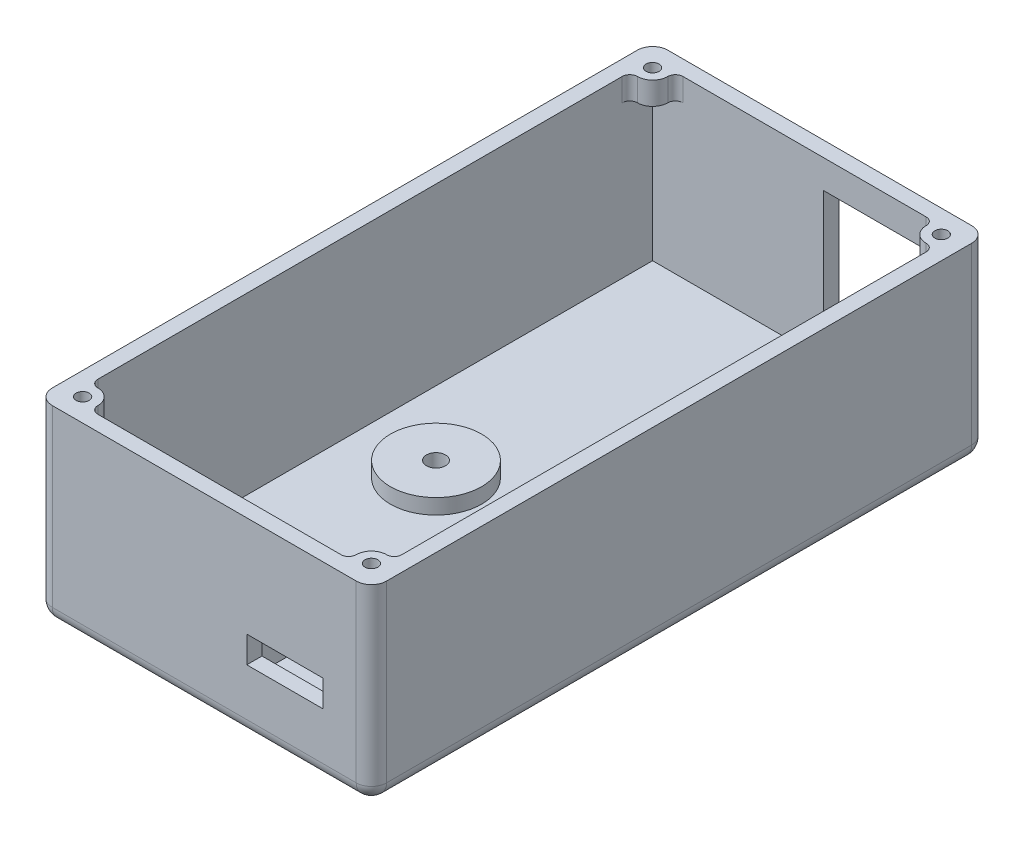
SolidWorks part; units mm, degrees
ref_plane "前视基准面" through (0, 0, 0) normal (0, 0, 1) x (1, 0, 0)
ref_plane "上视基准面" through (0, 0, 0) normal (0, 1, 0) x (1, 0, 0)
ref_plane "右视基准面" through (0, 0, 0) normal (1, 0, 0) x (0, 0, -1)
sketch "草图1" plane through (0, 0, 0) normal (0, 1, 0) x (1, 0, 0)
  line L1 (-22, 38) -> (22, 38)
  line L2 (-22, 38) -> (-22, -43)
  line L3 (-22, -43) -> (22, -43)
  line L4 (22, 38) -> (22, -43)
  dimension "D1" = 81
  dimension "D2" = 38
  dimension "D3" = 44
  dimension "D4" = 22
extrude "凸台-拉伸1" add sketch "草图1" along normal blind 25
shell "抽壳1" thickness 2
fillet "圆角1" radius 2 8 edges at (0, 0, -38) (0, 0, 43) (-22, 0, 2.5) (22, 0, 2.5) (-22, 12.5, 43) (-22, 12.5, -38) (22, 12.5, -38) (22, 12.5, 43)
sketch "草图2" plane through (0, 2, 0) normal (0, 1, 0) x (1, 0, 0)
  line L0 (20, 36) -> (-20, 36) construction
  line L1 (20, -41) -> (20, 36) construction
  line L2 (20, 36) -> (-20, 36) construction
  circle A0 centre (4.8, 16.9) radius 0.8
  circle A1 centre (16.1, -9.5) radius 0.9
  dimension "D1" = 19.1
  dimension "D3" = 45.5
  dimension "D2" = 15.2
  dimension "D4" = 3.9
extrude "切除-拉伸1" cut sketch "草图2" against normal blind 24
sketch "草图3" plane through (0, 2, 0) normal (0, 1, 0) x (1, 0, 0)
  line L1 (-20, 36) -> (-20, -41) construction
  line L2 (-20, -41) -> (20, -41) construction
  circle A0 centre (-9.5, -3) radius 1.25
  dimension "D3" = 2.5
  dimension "D1" = 10.5
  dimension "D2" = 38
extrude "切除-拉伸2" cut sketch "草图3" against normal blind 24
sketch "草图4" plane through (0, 2, 0) normal (0, 1, 0) x (1, 0, 0)
  circle A0 centre (-9.5, -3) radius 6
extrude "凸台-拉伸2" add sketch "草图4" along normal blind 2
sketch "草图6" plane through (0, 0, 0) normal (0, -1, 0) x (1, 0, 0)
  circle A0 centre (-9.5, 3) radius 1.25
extrude "切除-拉伸4" cut sketch "草图6" against normal blind 13.2
sketch "草图7" plane through (0, 0, -38) normal (0, 0, -1) x (-1, 0, 0)
  line L0 (20, 0) -> (-20, 0) construction
  line L1 (-18, 21.25) -> (-2.5, 21.25)
  line L2 (-18, 21.25) -> (-18, 3.75)
  line L3 (-18, 3.75) -> (-2.5, 3.75)
  line L4 (-2.5, 21.25) -> (-2.5, 3.75)
  line L5 (-22, 2) -> (-22, 25) construction
  dimension "D1" = 17.5
  dimension "D2" = 3.75
  dimension "D3" = 4
  dimension "D4" = 15.5
extrude "切除-拉伸5" cut sketch "草图7" against normal blind 13.2
sketch "草图9" plane through (0, 2, 0) normal (0, 1, 0) x (1, 0, 0)
  line L0 (-20, -41) -> (20, -41) construction
  line L1 (1.2, -34.5) -> (20, -34.5)
  line L2 (1.2, -34.5) -> (1.2, -41)
  line L3 (1.2, -41) -> (20, -41)
  line L4 (20, -34.5) -> (20, -41)
  line L5 (-20, -41) -> (20, -41) construction
  line L6 (22, -41) -> (22, 36) construction
  circle A0 centre (18.1, -37.9) radius 0.9
  circle A1 centre (3.1, -37.9) radius 0.9
  dimension "D7" = 1.8
  dimension "D8" = 1.8
  dimension "D1" = 15
  dimension "D2" = 1.9
  dimension "D3" = 3.1
  dimension "D4" = 6.5
  dimension "D5" = 1.9
  dimension "D6" = 2
  dimension "D9" = 3.1
  dimension "D10" = 18.8
extrude "凸台-拉伸3" add sketch "草图9" along normal blind 8 contours L2 L1 L4 L3 | A1 | A0
sketch "草图11" plane through (0, 10, 0) normal (0, 1, 0) x (1, 0, 0)
  line L0 (1.2, -34.5) -> (20, -34.5) construction
  line L1 (5.1, -34.5) -> (16.1, -34.5)
  line L2 (5.1, -34.5) -> (5.1, -41)
  line L3 (5.1, -41) -> (16.1, -41)
  line L4 (16.1, -34.5) -> (16.1, -41)
  line L5 (-20, -41) -> (20, -41) construction
  dimension "D1" = 11
  dimension "D2" = 3.9
extrude "切除-拉伸6" cut sketch "草图11" against normal blind 4
sketch "草图12" plane through (0, 0, 43) normal (0, 0, 1) x (1, 0, 0)
  line L0 (20, 0) -> (-20, 0) construction
  line L1 (5.6, 11.75) -> (15.6, 11.75)
  line L2 (5.6, 11.75) -> (5.6, 8.25)
  line L3 (5.6, 8.25) -> (15.6, 8.25)
  line L4 (15.6, 11.75) -> (15.6, 8.25)
  line L5 (22, 25) -> (22, 2) construction
  dimension "D1" = 10
  dimension "D2" = 3.5
  dimension "D3" = 8.25
  dimension "D4" = 6.4
extrude "切除-拉伸7" cut sketch "草图12" against normal blind 4
fillet "圆角2" radius 2 3 edges at (1.2, 2, 37.75) (10.6, 2, 34.5) (1.2, 6, 34.5)
sketch "草图14" plane through (0, 0, 0) normal (0, -1, 0) x (1, 0, 0)
  circle A0 centre (-9.5, 3) radius 1.25
extrude "凸台-拉伸4" add sketch "草图14" against normal blind 1
sketch "草图15" plane through (0, 0, 0) normal (0, -1, 0) x (1, 0, 0)
  circle A0 centre (16.1, 9.5) radius 2
  circle A1 centre (4.8, -16.9) radius 2
extrude "切除-拉伸8" cut sketch "草图15" against normal blind 1
sketch "草图17" plane through (0, 25, 0) normal (0, 1, 0) x (1, 0, 0)
  line L0 (20, 38) -> (-20, 38) construction
  line L1 (22, -41) -> (22, 36) construction
  line L2 (-30.1496, -2.5) -> (38.0021, -2.5) construction
  line L3 (0, 40.9857) -> (0, -45.3433) construction
  circle A0 centre (19, 35) radius 2
  circle A1 centre (-19, 35) radius 2
  circle A2 centre (-19, -40) radius 2
  circle A3 centre (19, -40) radius 2
  dimension "D1" = 4
  dimension "D2" = 3
  dimension "D3" = 3
  dimension "D4" = 40.5
extrude "凸台-拉伸5" add sketch "草图17" against normal blind 3
sketch "草图18" plane through (0, 25, 0) normal (0, 1, 0) x (1, 0, 0)
  line L0 (-31.1714, -2.5) -> (42.1346, -2.5) construction
  line L1 (0, 39.9209) -> (0, -19.3947) construction
  line L2 (20, 38) -> (-20, 38) construction
  circle A0 centre (19, 35) radius 0.85
  circle A1 centre (-19, 35) radius 0.85
  circle A2 centre (-19, -40) radius 0.85
  circle A3 centre (19, -40) radius 0.85
  dimension "D1" = 40.5
extrude "切除-拉伸10" cut sketch "草图18" against normal blind 3
fillet "圆角4" radius 1 8 edges at (20, 23.5, 38.2679) (17.2679, 23.5, 41) (-17.2679, 23.5, 41) (-20, 23.5, 38.2679) (17.2679, 23.5, -36) (20, 23.5, -33.2679) (-17.2679, 23.5, -36) (-20, 23.5, -33.2679)
